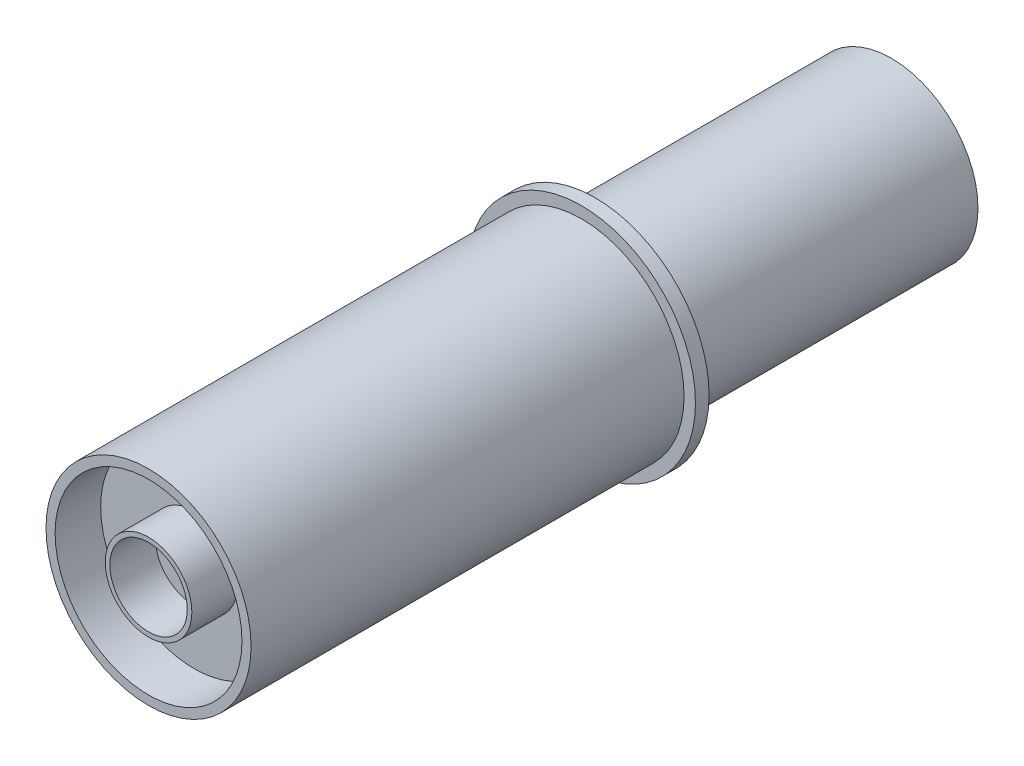
SolidWorks part; units mm, degrees
ref_plane "Front Plane" through (0, 0, 0) normal (0, 0, 1) x (1, 0, 0)
ref_plane "Top Plane" through (0, 0, 0) normal (0, 1, 0) x (1, 0, 0)
ref_plane "Right Plane" through (0, 0, 0) normal (1, 0, 0) x (0, 0, -1)
sketch "Sketch1" plane through (0, 0, 0) normal (0, 0, 1) x (1, 0, 0)
  circle A0 centre (-114.1668, 45.6667) radius 19
  dimension "D1" = 38
extrude "Boss-Extrude1" add sketch "Sketch1" along normal blind 65
sketch "Sketch2" plane through (0, 0, 65) normal (0, 0, 1) x (1, 0, 0)
  circle A0 centre (-114.1668, 45.6667) radius 25
  circle A1 centre (-114.1668, 45.6667) radius 19 construction
  dimension "D1" = 50
extrude "Boss-Extrude2" add sketch "Sketch2" along normal blind 3
sketch "Sketch3" plane through (0, 0, 68) normal (0, 0, 1) x (1, 0, 0)
  circle A0 centre (-114.1668, 45.6667) radius 22.5
  circle A3 centre (-114.1668, 45.6667) radius 25 construction
  dimension "D1" = 45
extrude "Boss-Extrude3" add sketch "Sketch3" along normal blind 95
sketch "Sketch4" plane through (0, 0, 163) normal (0, 0, 1) x (1, 0, 0)
  circle A0 centre (-114.1668, 45.6667) radius 20.5
  circle A1 centre (-114.1668, 45.6667) radius 22.5 construction
  dimension "D1" = 2
extrude "Cut-Extrude1" cut sketch "Sketch4" against normal blind 10
sketch "Sketch5" plane through (0, 0, 153) normal (0, 0, 1) x (1, 0, 0)
  circle A0 centre (-114.1668, 45.6667) radius 9.5
  circle A1 centre (-114.1668, 45.6667) radius 8.5
  circle A2 centre (-114.1668, 45.6667) radius 20.5 construction
  dimension "D1" = 19
  dimension "D2" = 1
extrude "Boss-Extrude4" add sketch "Sketch5" along normal blind 10
